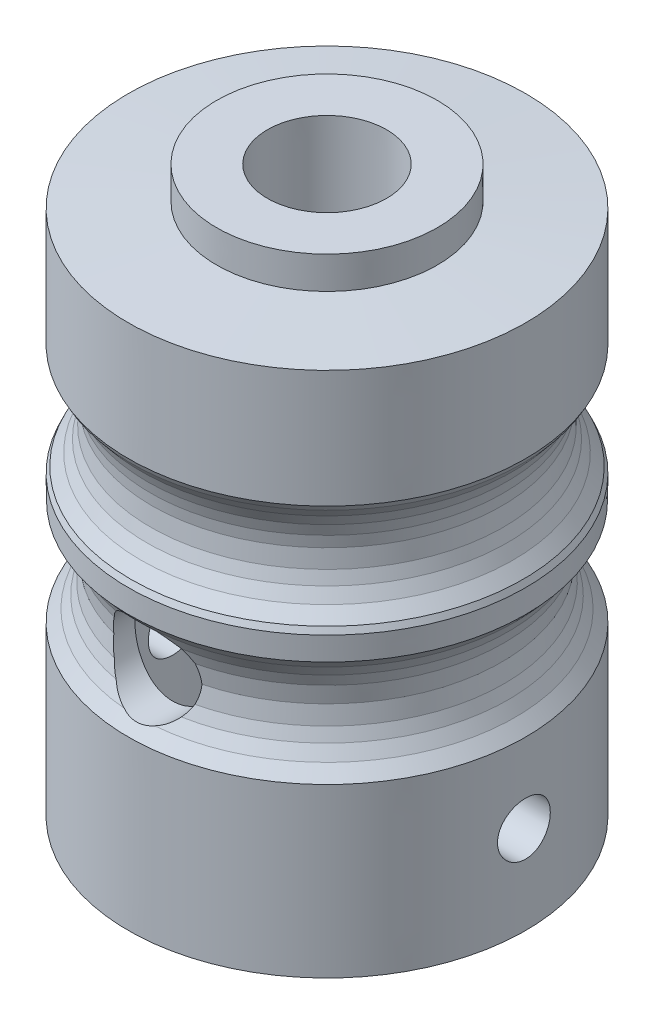
SolidWorks part; units mm, degrees
ref_plane "Front Plane" through (0, 0, 0) normal (0, 0, 1) x (1, 0, 0)
ref_plane "Top Plane" through (0, 0, 0) normal (0, 1, 0) x (1, 0, 0)
ref_plane "Right Plane" through (0, 0, 0) normal (1, 0, 0) x (0, 0, -1)
sketch "CADView Revolve Profile" plane through (0, 0, 0) normal (0, 0, 1) x (1, 0, 0)
  line L1 (11.1914, 0) -> (11.1917, 9.4414)
  line L2 (11.1917, 9.4414) -> (10.6005, 10.104)
  line L3 (10.6005, 10.104) -> (10.2111, 10.7666)
  line L4 (10.2111, 10.7666) -> (9.974, 11.4291)
  line L5 (9.974, 11.4291) -> (9.8443, 12.423)
  line L6 (9.8443, 12.423) -> (9.9678, 13.4168)
  line L7 (9.9678, 13.4168) -> (10.1998, 14.0793)
  line L8 (10.1998, 14.0793) -> (10.583, 14.7419)
  line L9 (10.583, 14.7419) -> (11.1765, 15.4045)
  line L10 (11.1765, 15.4045) -> (11.1915, 16.7296)
  line L11 (11.1915, 16.7296) -> (11.0446, 17.0609)
  line L12 (11.0446, 17.0609) -> (10.4903, 17.7234)
  line L13 (10.4903, 17.7234) -> (10.1428, 18.386)
  line L14 (10.1428, 18.386) -> (9.9363, 19.0485)
  line L15 (9.9363, 19.0485) -> (9.8474, 20.0424)
  line L16 (9.8474, 20.0424) -> (9.928, 20.7049)
  line L17 (9.928, 20.7049) -> (10.1272, 21.3675)
  line L18 (10.1272, 21.3675) -> (10.4647, 22.03)
  line L19 (10.4647, 22.03) -> (11.0062, 22.6926)
  line L20 (11.0062, 22.6926) -> (11.1915, 23.0239)
  line L21 (11.1915, 23.0239) -> (11.1915, 29.6495)
  line L22 (11.1915, 29.6495) -> (6.2175, 29.9807)
  line L23 (6.2175, 29.9807) -> (6.2174, 31.8028)
  line L24 (6.2174, 31.8028) -> (3.3572, 31.8028)
  line L25 (3.3572, 31.8028) -> (3.3573, 26.0054)
  line L26 (3.3573, 26.0054) -> (8.7043, 25.6741)
  line L27 (8.7043, 25.6741) -> (8.7042, 0)
  line L28 (8.7042, 0) -> (11.1914, 0)
  line L29 (0, 0) -> (0, 31.8028) construction
revolve "CADView Core Revolve" add sketch "CADView Revolve Profile" angle 360 about L29
sketch "CADView Radial Hole Profile 1" plane through (0, 0, 0) normal (0, 0, 1) x (1, 0, 0)
  circle A0 centre (0.0001, 19.8964) radius 2.4829
extrude "CADView Radial Hole 1" cut sketch "CADView Radial Hole Profile 1" against normal mid plane 2.4223 from offset 9.5279
sketch "CADView Radial Hole Profile 3" plane through (0, 0, 0) normal (1, 0, 0) x (0, 0, -1)
  circle A0 centre (0.0001, 4.9744) radius 1.4879
extrude "CADView Radial Hole 3" cut sketch "CADView Radial Hole Profile 3" against normal mid plane 2.6682 from offset 9.884
sketch "CADView Radial Hole Profile 2" plane through (0, 0, 0) normal (0, 0, 1) x (1, 0, 0)
  circle A0 centre (0.0003, 12.4354) radius 2.4829
extrude "CADView Radial Hole 2" cut sketch "CADView Radial Hole Profile 2" against normal mid plane 2.4233 from offset 9.5294
sketch "CADView Radial Hole Profile 4" plane through (0, 0, 0) normal (1, 0, 0) x (0, 0, -1)
  circle A0 centre (0, 4.974) radius 1.4877
extrude "CADView Radial Hole 4" cut sketch "CADView Radial Hole Profile 4" against normal mid plane 2.668 from offset 9.8832
